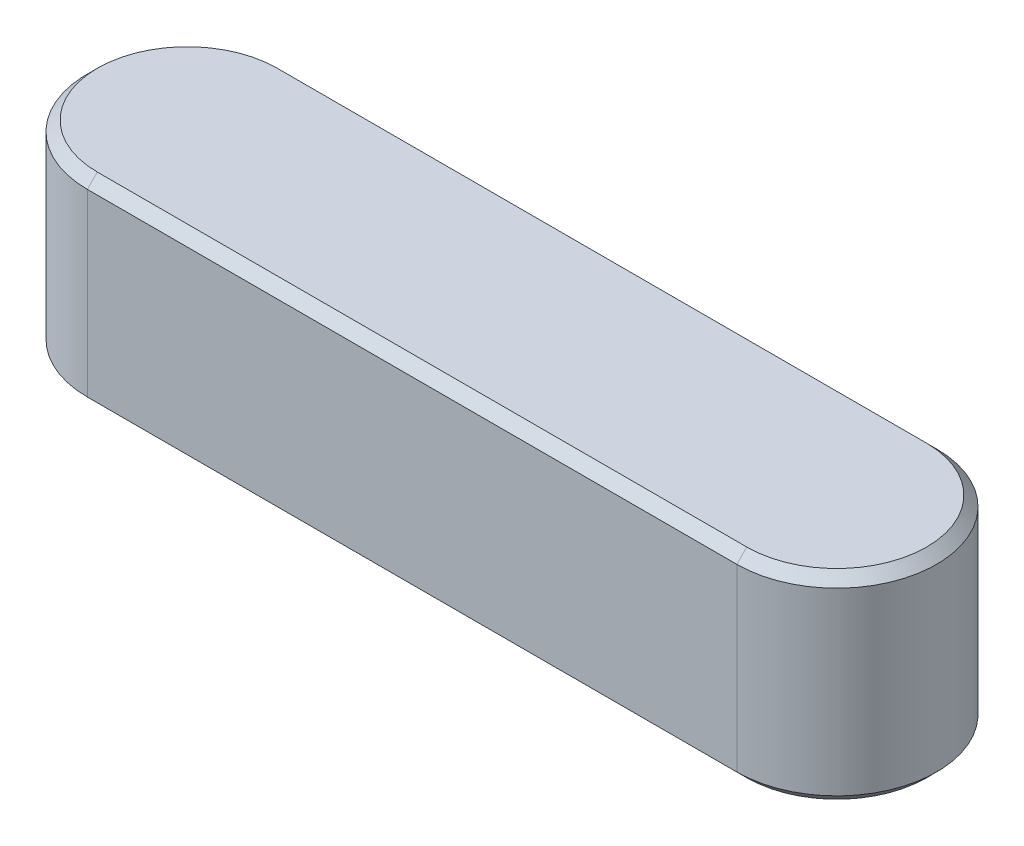
SolidWorks part; units mm, degrees
ref_plane "Front" through (0, 0, 0) normal (0, 0, 1) x (1, 0, 0)
ref_plane "Top" through (0, 0, 0) normal (0, 1, 0) x (1, 0, 0)
ref_plane "Right" through (0, 0, 0) normal (1, 0, 0) x (0, 0, -1)
sketch "Sketch1" plane through (0, 0, 0) normal (0, 1, 0) x (1, 0, 0)
  line L0 (0, 0) -> (6, 0) construction
  line L1 (0, 2) -> (6, 2)
  line L2 (0, -2) -> (6, -2)
  arc A0 (0, 2) -> (0, -2) centre (0, 0) ccw
  arc A1 (6, -2) -> (6, 2) centre (6, 0) ccw
  point P3 (3, 0)
  dimension "D1" = 2
  dimension "D2" = 6
extrude "Boss-Extrude1" [suppressed] add sketch "Sketch1" along normal blind 4
sketch "Sketch2" plane through (0, 0, 0) normal (0, 1, 0) x (1, 0, 0)
  line L0 (0, 0) -> (13, 0) construction
  line L1 (0, 2) -> (13, 2)
  line L2 (0, -2) -> (13, -2)
  arc A0 (0, 2) -> (0, -2) centre (0, 0) ccw
  arc A1 (13, -2) -> (13, 2) centre (13, 0) ccw
  point P3 (6.5, 0)
  dimension "D1" = 2
  dimension "D2" = 13
extrude "Boss-Extrude2" add sketch "Sketch2" along normal blind 4
chamfer "Chamfer1" [suppressed] distance 0.2 angle 45
chamfer "Chamfer2" distance 0.2 angle 45 8 edges at (6.5, 0, 2) (15, 0, 0) (6.5, 0, -2) (-2, 0, 0) (6.5, 4, -2) (15, 4, 0) (6.5, 4, 2) (-2, 4, 0)
